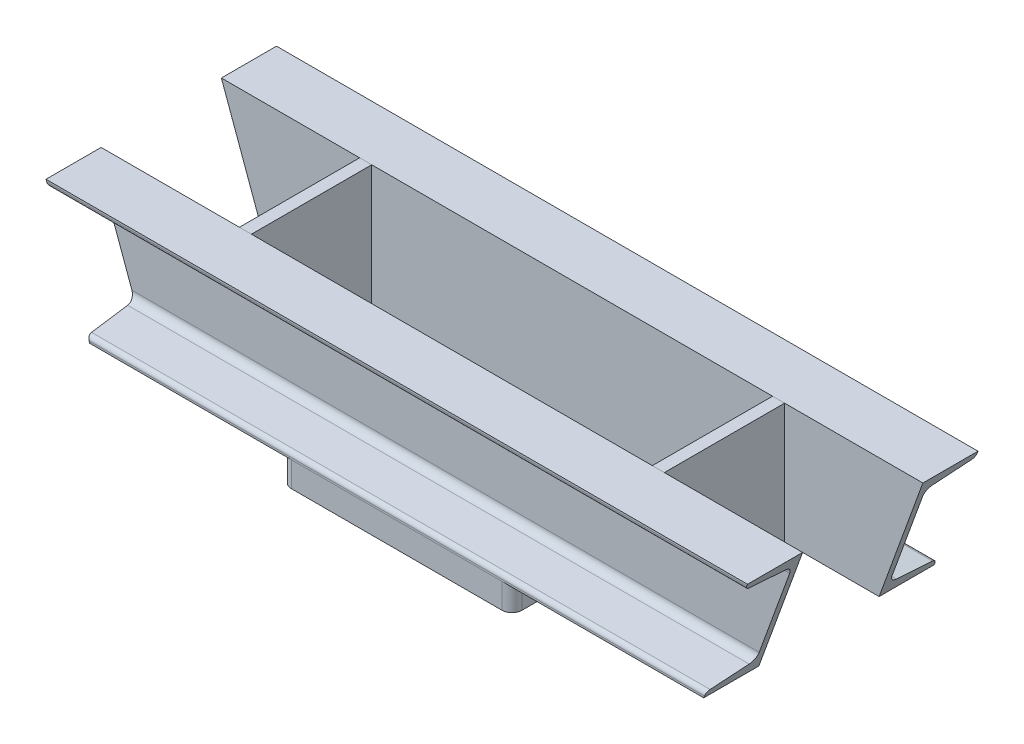
SolidWorks part; units mm, degrees
ref_plane "Front Plane" through (0, 0, 0) normal (0, 0, 1) x (1, 0, 0)
ref_plane "Top Plane" through (0, 0, 0) normal (0, 1, 0) x (1, 0, 0)
ref_plane "Right Plane" through (0, 0, 0) normal (1, 0, 0) x (0, 0, -1)
sketch "Sketch3" plane through (0, 0, 0) normal (0, 1, 0) x (1, 0, 0)
  line L0 (-350, 60) -> (350, 60)
  line L2 (-350, -60) -> (350, -60)
  dimension "D1" = 700
  dimension "D2" = 350
  dimension "D3" = 60
  dimension "D4" = 60
  dimension "D5" = 700
  dimension "D6" = 350
other "C channel 120 X 12(1)"
ref_plane "Plane1" through (-350, 0, 60) normal (1, 0, 0) x (0, 0, 1)
sketch "Sketch1" plane through (-350, 0, 60) normal (1, 0, 0) x (0, 0, 1)
  line L0 (55, 120) -> (0, 120)
  line L1 (55, 0) -> (0, 0)
  line L2 (0, 120) -> (0, 0)
  line L6 (55, 120) -> (55, 118.1136)
  line L7 (55, 0) -> (55, 1.8964)
  line L12 (6.3, 101.74) -> (6.3, 18.27)
  line L17 (13.4638, 109.6962) -> (50.9704, 113.6383)
  line L18 (13.4638, 10.3138) -> (50.9704, 6.3717)
  arc A0 (50.9704, 113.6383) -> (55, 118.1136) centre (50.5, 118.1136) ccw
  arc A1 (50.9704, 6.3717) -> (55, 1.8964) centre (50.5, 1.8964) cw
  arc A9 (6.3, 18.27) -> (13.4638, 10.3138) centre (14.3, 18.27) ccw
  arc A10 (6.3, 101.74) -> (13.4638, 109.6962) centre (14.3, 101.74) cw
  point P8 (0, 60)
  point P9 (6.3, 60.005)
  point P10 (27.5, 120)
  point P11 (27.5, 0)
  point P12 (55, 5.9482)
  point P13 (55, 114.0618)
  point P14 (0, 0)
  dimension "D4" = 4.5
  dimension "RI" = 8
  dimension "D2" = 6
  dimension "D3" = 18.26
  dimension "Depth" = 120
  dimension "BF" = 55
  dimension "TW" = 6.3
  dimension "d1" = 83.47
other "C channel 120 X 12(2)"
ref_plane "Plane2" through (-350, 0, -60) normal (-1, 0, 0) x (0, 0, -1)
sketch "Sketch11" plane through (-350, 0, -60) normal (-1, 0, 0) x (0, 0, -1)
  line L0 (55, 120) -> (0, 120)
  line L1 (55, 0) -> (0, 0)
  line L2 (0, 120) -> (0, 0)
  line L6 (55, 120) -> (55, 118.1136)
  line L7 (55, 0) -> (55, 1.8964)
  line L12 (6.3, 101.74) -> (6.3, 18.27)
  line L17 (13.4638, 109.6962) -> (50.9704, 113.6383)
  line L18 (13.4638, 10.3138) -> (50.9704, 6.3717)
  arc A0 (50.9704, 113.6383) -> (55, 118.1136) centre (50.5, 118.1136) ccw
  arc A1 (50.9704, 6.3717) -> (55, 1.8964) centre (50.5, 1.8964) cw
  arc A9 (6.3, 18.27) -> (13.4638, 10.3138) centre (14.3, 18.27) ccw
  arc A10 (6.3, 101.74) -> (13.4638, 109.6962) centre (14.3, 101.74) cw
  point P8 (0, 60)
  point P9 (6.3, 60.005)
  point P10 (27.5, 120)
  point P11 (27.5, 0)
  point P12 (55, 5.9482)
  point P13 (55, 114.0618)
  point P14 (0, 0)
  dimension "D4" = 4.5
  dimension "RI" = 8
  dimension "D2" = 6
  dimension "D3" = 18.26
  dimension "Depth" = 120
  dimension "BF" = 55
  dimension "TW" = 6.3
  dimension "d1" = 83.47
sketch "Sketch13" plane through (0, 0, -60) normal (0, 0, 1) x (1, 0, 0)
  line L0 (350, -120) -> (-350, -120) construction
  line L1 (-212, 0) -> (-200, 0)
  line L2 (-212, 0) -> (-212, -120)
  line L3 (-212, -120) -> (-200, -120)
  line L4 (-200, 0) -> (-200, -120)
  line L5 (-350, 0) -> (350, 0) construction
  line L6 (200, 0) -> (212, 0)
  line L7 (200, 0) -> (200, -120)
  line L8 (200, -120) -> (212, -120)
  line L9 (212, 0) -> (212, -120)
  point P12 (0, 0)
  dimension "D1" = 12
  dimension "D2" = 12
  dimension "D3" = 200
  dimension "D4" = 200
extrude "Boss-Extrude1" add sketch "Sketch13" along normal up to next separate body
sketch "Sketch15" plane through (0, -120, 0) normal (0, -1, 0) x (1, 0, 0)
  line L0 (350, 115) -> (-350, 115) construction
  line L1 (-105, -115) -> (105, -115)
  line L2 (-115, -105) -> (-115, 105)
  line L3 (-105, 115) -> (105, 115)
  line L4 (115, -105) -> (115, 105)
  line L5 (-115, -115) -> (115, 115) construction
  line L6 (-115, 115) -> (115, -115) construction
  arc A0 (-105, -115) -> (-115, -105) centre (-105, -105) cw
  arc A1 (105, -115) -> (115, -105) centre (105, -105) ccw
  arc A2 (105, 115) -> (115, 105) centre (105, 105) cw
  arc A3 (-115, 105) -> (-105, 115) centre (-105, 105) cw
  point P0 (0, 0)
  dimension "D2" = 10
  dimension "D1" = 230
extrude "Boss-Extrude3" add sketch "Sketch15" along normal blind 25 separate body
sketch "Sketch16" plane through (0, -145, 0) normal (0, -1, 0) x (1, 0, 0)
  circle A0 centre (0, 0) radius 40
  dimension "D1" = 80
extrude "Cut-Extrude2" cut sketch "Sketch16" against normal up to next (25 mm away)
sketch "Sketch17" plane through (0, 0, 0) normal (0, 0, 1) x (1, 0, 0)
  line L0 (-350, 0) -> (-350, -120)
  line L1 (-350, -120) -> (-306.3236, -120)
  line L2 (350, -120) -> (-350, -120) construction
  line L3 (-306.3236, -120) -> (-350, 0)
  line L4 (350, 0) -> (350, -120)
  line L5 (-350, 0) -> (350, 0) construction
  line L6 (-350, 0) -> (350, 0) construction
  line L7 (350, -120) -> (306.3236, -120)
  line L8 (306.3236, -120) -> (350, 0)
  dimension "D1" = 20
  dimension "D2" = 20
extrude "Cut-Extrude3" cut sketch "Sketch17" against normal through all both and the other way through all
